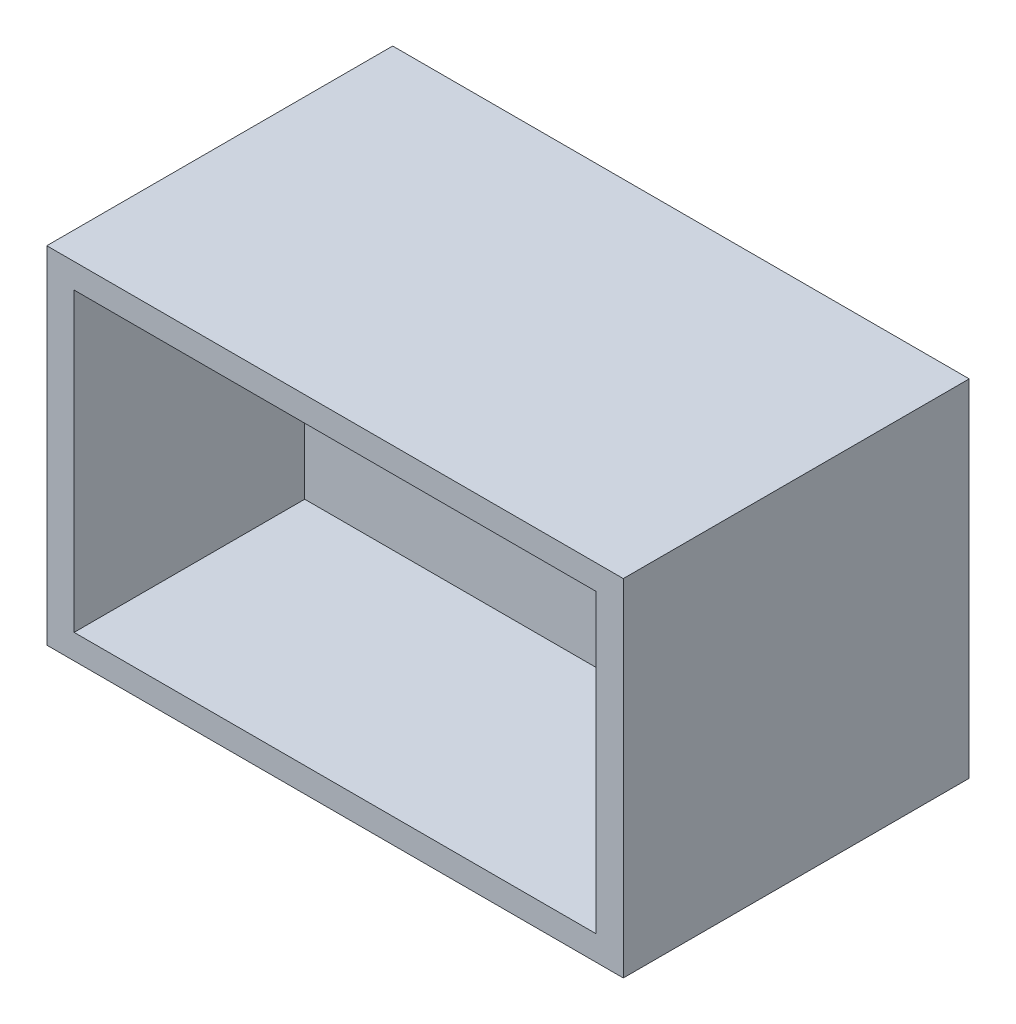
SolidWorks part; units mm, degrees
ref_plane "Front Plane" through (0, 0, 0) normal (0, 0, 1) x (1, 0, 0)
ref_plane "Top Plane" through (0, 0, 0) normal (0, 1, 0) x (1, 0, 0)
ref_plane "Right Plane" through (0, 0, 0) normal (1, 0, 0) x (0, 0, -1)
sketch "Sketch1" plane through (0, 0, 0) normal (0, 0, 1) x (1, 0, 0)
  line L0 (-1.842, -2.0122) -> (3.158, -2.0122)
  line L1 (-1.842, -2.0122) -> (-1.842, 0.9878)
  line L2 (-1.842, 0.9878) -> (3.158, 0.9878)
  line L3 (3.158, -2.0122) -> (3.158, 0.9878)
  line L4 (-1.842, -2.0122) -> (3.158, 0.9878) construction
  line L5 (-1.842, 0.9878) -> (3.158, -2.0122) construction
  point P0 (0.658, -0.5122)
extrude "Boss-Extrude1" add sketch "Sketch1" along normal blind 3
sketch "Sketch3" plane through (0, 0, 3) normal (0, 0, 1) x (1, 0, 0)
  line L1 (-1.605, -1.7978) -> (2.9209, -1.7978)
  line L2 (-1.605, -1.7978) -> (-1.605, 0.7734)
  line L3 (-1.605, 0.7734) -> (2.9209, 0.7734)
  line L4 (2.9209, -1.7978) -> (2.9209, 0.7734)
  line L5 (-1.605, -1.7978) -> (2.9209, 0.7734) construction
  line L6 (-1.605, 0.7734) -> (2.9209, -1.7978) construction
  point P0 (0.658, -0.5122)
extrude "Cut-Extrude1" cut sketch "Sketch3" against normal blind 2
